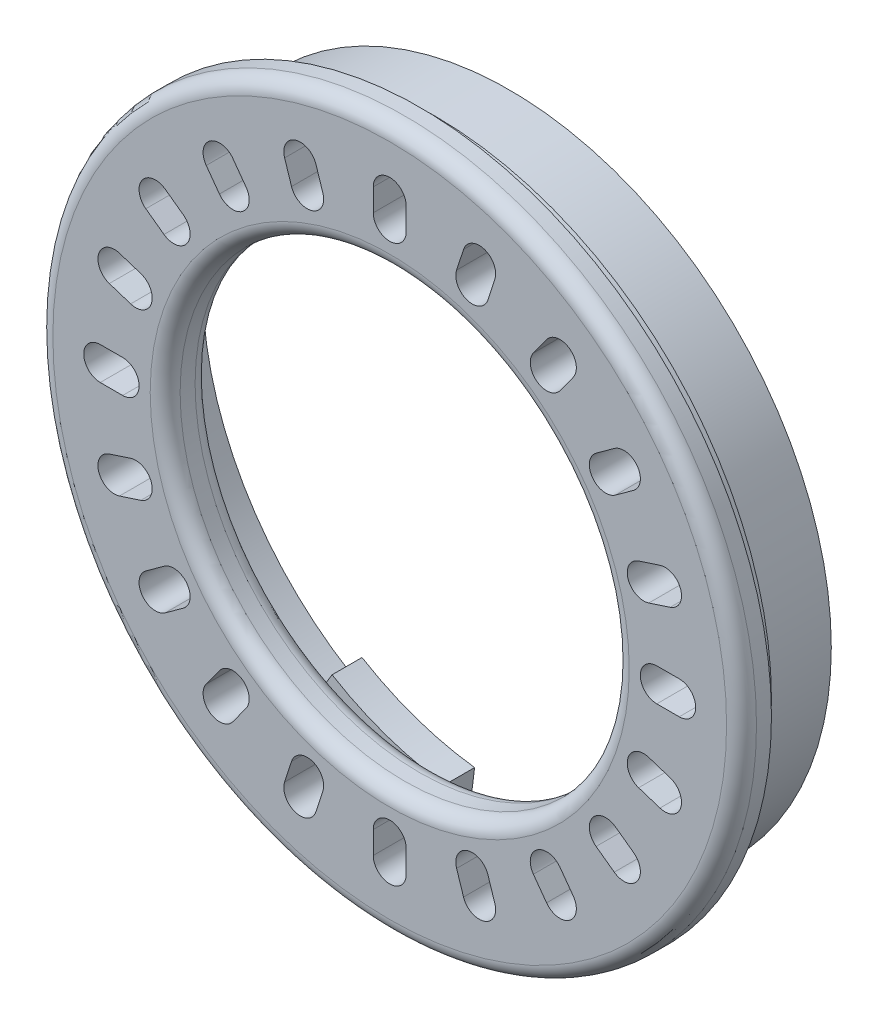
SolidWorks part; units mm, degrees
ref_plane "前视基准面" through (0, 0, 0) normal (0, 0, 1) x (1, 0, 0)
ref_plane "上视基准面" through (0, 0, 0) normal (0, 1, 0) x (1, 0, 0)
ref_plane "右视基准面" through (0, 0, 0) normal (1, 0, 0) x (0, 0, -1)
sketch "草图1" plane through (0, 0, 0) normal (0, 0, 1) x (1, 0, 0)
  circle A0 centre (0, 0) radius 23.5157
  circle A2 centre (0, 0) radius 15.01
  dimension "D1" = 30.02
extrude "凸台-拉伸1" add sketch "草图1" along normal blind 3
sketch "草图2" plane through (0, 0, 0) normal (0, 0, -1) x (-1, 0, 0)
  circle A7 centre (0, 0) radius 22.5157
  circle A8 centre (0, 0) radius 23.5157
  circle A9 centre (0, 0) radius 23.5157
  dimension "D1" = 0
  dimension "D2" = 1
extrude "切除-拉伸3" cut sketch "草图2" against normal blind 1
fillet "圆角1" radius 1 1 edges at (23.5157, 0, 3)
fillet "圆角2" radius 1 1 edges at (15.01, 0, 3)
fillet "圆角3" radius 1 1 edges at (15.01, 0, 0)
sketch "草图3" plane through (0, 0, 3) normal (0, 0, 1) x (1, 0, 0)
  line L0 (5.9795, 18.4029) -> (5.516, 16.9764) construction
  line L1 (0, 19.35) -> (0, 17.85) construction
  line L2 (1.1, 19.35) -> (1.1, 17.85)
  line L5 (-1.1, 19.35) -> (-1.1, 17.85)
  line L8 (7.0256, 18.063) -> (6.5621, 16.6364)
  line L17 (4.9333, 18.7429) -> (4.4698, 17.3163)
  line L26 (11.3736, 15.6545) -> (10.492, 14.441) construction
  line L35 (12.2636, 15.0079) -> (11.3819, 13.7944)
  line L44 (10.4837, 16.301) -> (9.602, 15.0875)
  line L53 (15.6545, 11.3736) -> (14.441, 10.492) construction
  line L62 (16.301, 10.4837) -> (15.0875, 9.602)
  line L65 (15.0079, 12.2636) -> (13.7944, 11.3819)
  line L68 (18.4029, 5.9795) -> (16.9764, 5.516) construction
  line L71 (18.7429, 4.9333) -> (17.3163, 4.4698)
  line L74 (18.063, 7.0256) -> (16.6364, 6.5621)
  line L77 (19.35, 0) -> (17.85, 0) construction
  line L80 (19.35, -1.1) -> (17.85, -1.1)
  line L83 (19.35, 1.1) -> (17.85, 1.1)
  line L86 (18.4029, -5.9795) -> (16.9764, -5.516) construction
  line L89 (18.063, -7.0256) -> (16.6364, -6.5621)
  line L92 (18.7429, -4.9333) -> (17.3163, -4.4698)
  line L95 (15.6545, -11.3736) -> (14.441, -10.492) construction
  line L98 (15.0079, -12.2636) -> (13.7944, -11.3819)
  line L101 (16.301, -10.4837) -> (15.0875, -9.602)
  line L102 (11.3736, -15.6545) -> (10.492, -14.441) construction
  line L103 (10.4837, -16.301) -> (9.602, -15.0875)
  line L104 (12.2636, -15.0079) -> (11.3819, -13.7944)
  line L105 (5.9795, -18.4029) -> (5.516, -16.9764) construction
  line L106 (4.9333, -18.7429) -> (4.4698, -17.3163)
  line L107 (7.0256, -18.063) -> (6.5621, -16.6364)
  line L108 (0, -19.35) -> (0, -17.85) construction
  line L109 (-1.1, -19.35) -> (-1.1, -17.85)
  line L110 (1.1, -19.35) -> (1.1, -17.85)
  line L111 (-5.9795, -18.4029) -> (-5.516, -16.9764) construction
  line L112 (-7.0256, -18.063) -> (-6.5621, -16.6364)
  line L113 (-4.9333, -18.7429) -> (-4.4698, -17.3163)
  line L114 (-11.3736, -15.6545) -> (-10.492, -14.441) construction
  line L115 (-12.2636, -15.0079) -> (-11.3819, -13.7944)
  line L116 (-10.4837, -16.301) -> (-9.602, -15.0875)
  line L117 (-15.6545, -11.3736) -> (-14.441, -10.492) construction
  line L118 (-16.301, -10.4837) -> (-15.0875, -9.602)
  line L119 (-15.0079, -12.2636) -> (-13.7944, -11.3819)
  line L120 (-18.4029, -5.9795) -> (-16.9764, -5.516) construction
  line L121 (-18.7429, -4.9333) -> (-17.3163, -4.4698)
  line L122 (-18.063, -7.0256) -> (-16.6364, -6.5621)
  line L123 (-19.35, 0) -> (-17.85, 0) construction
  line L124 (-19.35, 1.1) -> (-17.85, 1.1)
  line L125 (-19.35, -1.1) -> (-17.85, -1.1)
  line L126 (-18.4029, 5.9795) -> (-16.9764, 5.516) construction
  line L127 (-18.063, 7.0256) -> (-16.6364, 6.5621)
  line L128 (-18.7429, 4.9333) -> (-17.3163, 4.4698)
  line L129 (-15.6545, 11.3736) -> (-14.441, 10.492) construction
  line L130 (-15.0079, 12.2636) -> (-13.7944, 11.3819)
  line L131 (-16.301, 10.4837) -> (-15.0875, 9.602)
  line L132 (-11.3736, 15.6545) -> (-10.492, 14.441) construction
  line L133 (-10.4837, 16.301) -> (-9.602, 15.0875)
  line L134 (-12.2636, 15.0079) -> (-11.3819, 13.7944)
  line L135 (-5.9795, 18.4029) -> (-5.516, 16.9764) construction
  line L136 (-4.9333, 18.7429) -> (-4.4698, 17.3163)
  line L137 (-7.0256, 18.063) -> (-6.5621, 16.6364)
  arc A42 (1.1, 19.35) -> (-1.1, 19.35) centre (0, 19.35) ccw
  arc A43 (-1.1, 17.85) -> (1.1, 17.85) centre (0, 17.85) ccw
  circle A82 centre (0, 0) radius 16.01 construction
  arc A83 (7.0256, 18.063) -> (4.9333, 18.7429) centre (5.9795, 18.4029) ccw
  arc A84 (4.4698, 17.3163) -> (6.5621, 16.6364) centre (5.516, 16.9764) ccw
  arc A85 (12.2636, 15.0079) -> (10.4837, 16.301) centre (11.3736, 15.6545) ccw
  arc A86 (9.602, 15.0875) -> (11.3819, 13.7944) centre (10.492, 14.441) ccw
  arc A87 (16.301, 10.4837) -> (15.0079, 12.2636) centre (15.6545, 11.3736) ccw
  arc A88 (13.7944, 11.3819) -> (15.0875, 9.602) centre (14.441, 10.492) ccw
  arc A89 (18.7429, 4.9333) -> (18.063, 7.0256) centre (18.4029, 5.9795) ccw
  arc A90 (16.6364, 6.5621) -> (17.3163, 4.4698) centre (16.9764, 5.516) ccw
  arc A91 (19.35, -1.1) -> (19.35, 1.1) centre (19.35, 0) ccw
  arc A92 (17.85, 1.1) -> (17.85, -1.1) centre (17.85, 0) ccw
  arc A93 (18.063, -7.0256) -> (18.7429, -4.9333) centre (18.4029, -5.9795) ccw
  arc A94 (17.3163, -4.4698) -> (16.6364, -6.5621) centre (16.9764, -5.516) ccw
  arc A95 (15.0079, -12.2636) -> (16.301, -10.4837) centre (15.6545, -11.3736) ccw
  arc A96 (15.0875, -9.602) -> (13.7944, -11.3819) centre (14.441, -10.492) ccw
  arc A97 (10.4837, -16.301) -> (12.2636, -15.0079) centre (11.3736, -15.6545) ccw
  arc A98 (11.3819, -13.7944) -> (9.602, -15.0875) centre (10.492, -14.441) ccw
  arc A99 (4.9333, -18.7429) -> (7.0256, -18.063) centre (5.9795, -18.4029) ccw
  arc A100 (6.5621, -16.6364) -> (4.4698, -17.3163) centre (5.516, -16.9764) ccw
  arc A101 (-1.1, -19.35) -> (1.1, -19.35) centre (0, -19.35) ccw
  arc A102 (1.1, -17.85) -> (-1.1, -17.85) centre (0, -17.85) ccw
  arc A103 (-7.0256, -18.063) -> (-4.9333, -18.7429) centre (-5.9795, -18.4029) ccw
  arc A104 (-4.4698, -17.3163) -> (-6.5621, -16.6364) centre (-5.516, -16.9764) ccw
  arc A105 (-12.2636, -15.0079) -> (-10.4837, -16.301) centre (-11.3736, -15.6545) ccw
  arc A106 (-9.602, -15.0875) -> (-11.3819, -13.7944) centre (-10.492, -14.441) ccw
  arc A107 (-16.301, -10.4837) -> (-15.0079, -12.2636) centre (-15.6545, -11.3736) ccw
  arc A108 (-13.7944, -11.3819) -> (-15.0875, -9.602) centre (-14.441, -10.492) ccw
  arc A109 (-18.7429, -4.9333) -> (-18.063, -7.0256) centre (-18.4029, -5.9795) ccw
  arc A110 (-16.6364, -6.5621) -> (-17.3163, -4.4698) centre (-16.9764, -5.516) ccw
  arc A111 (-19.35, 1.1) -> (-19.35, -1.1) centre (-19.35, 0) ccw
  arc A112 (-17.85, -1.1) -> (-17.85, 1.1) centre (-17.85, 0) ccw
  arc A113 (-18.063, 7.0256) -> (-18.7429, 4.9333) centre (-18.4029, 5.9795) ccw
  arc A114 (-17.3163, 4.4698) -> (-16.6364, 6.5621) centre (-16.9764, 5.516) ccw
  arc A115 (-15.0079, 12.2636) -> (-16.301, 10.4837) centre (-15.6545, 11.3736) ccw
  arc A116 (-15.0875, 9.602) -> (-13.7944, 11.3819) centre (-14.441, 10.492) ccw
  arc A117 (-10.4837, 16.301) -> (-12.2636, 15.0079) centre (-11.3736, 15.6545) ccw
  arc A118 (-11.3819, 13.7944) -> (-9.602, 15.0875) centre (-10.492, 14.441) ccw
  arc A119 (-4.9333, 18.7429) -> (-7.0256, 18.063) centre (-5.9795, 18.4029) ccw
  arc A120 (-6.5621, 16.6364) -> (-4.4698, 17.3163) centre (-5.516, 16.9764) ccw
  point P7 (5.7477, 17.6897)
  point P9 (0, 18.6)
  point P20 (10.9328, 15.0477)
  point P27 (15.0477, 10.9328)
  point P34 (17.6897, 5.7477)
  point P41 (18.6, 0)
  point P48 (17.6897, -5.7477)
  point P55 (15.0477, -10.9328)
  point P62 (10.9328, -15.0477)
  point P69 (5.7477, -17.6897)
  point P76 (0, -18.6)
  point P83 (-5.7477, -17.6897)
  point P90 (-10.9328, -15.0477)
  point P97 (-15.0477, -10.9328)
  point P104 (-17.6897, -5.7477)
  point P111 (-18.6, 0)
  point P118 (-17.6897, 5.7477)
  point P125 (-15.0477, 10.9328)
  point P132 (-10.9328, 15.0477)
  point P139 (-5.7477, 17.6897)
  point P144 (0, 0)
  point P150 (-0.7039, -0.6961)
  dimension "D1" = 1.5
  dimension "D3" = 2.2
  dimension "D4" = 18.6
extrude "切除-拉伸4" cut sketch "草图3" against normal through all
sketch "草图5" plane through (0, 0, 0) normal (0, 0, -1) x (-1, 0, 0)
  circle A0 centre (0, 0) radius 20.5157
  circle A1 centre (0, 0) radius 21.5157
  circle A3 centre (0, 0) radius 22.5157 construction
  dimension "D1" = 1
  dimension "D2" = 1
extrude "凸台-拉伸2" add sketch "草图5" along normal blind 5
sketch "草图6" plane through (0, 0, -5) normal (0, 0, -1) x (-1, 0, 0)
  line L6 (-16.2691, -9.8527) -> (-18.354, -11.1153)
  line L7 (-18.8771, -2.3269) -> (-21.2962, -2.6251)
  line L8 (-9.8527, 16.2691) -> (-11.1153, 18.354)
  line L9 (-2.3269, 18.8771) -> (-2.6251, 21.2962)
  line L10 (16.2691, 9.8527) -> (18.354, 11.1153)
  line L11 (18.8771, 2.3269) -> (21.2962, 2.6251)
  line L12 (9.8527, -16.2691) -> (11.1153, -18.354)
  line L13 (2.3269, -18.8771) -> (2.6251, -21.2962)
  arc A0 (-21.2962, -2.6251) -> (-18.354, -11.1153) centre (0, 0) ccw
  arc A1 (-18.8771, -2.3269) -> (-16.2691, -9.8527) centre (0, 0) ccw
  arc A2 (-18.825, -2.573) -> (-18.4502, -4.5376) centre (0, 0) ccw construction
  arc A7 (-2.6251, 21.2962) -> (-11.1153, 18.354) centre (0, 0) ccw
  arc A8 (-2.3269, 18.8771) -> (-9.8527, 16.2691) centre (0, 0) ccw
  arc A9 (21.2962, 2.6251) -> (18.354, 11.1153) centre (0, 0) ccw
  arc A10 (18.8771, 2.3269) -> (16.2691, 9.8527) centre (0, 0) ccw
  arc A11 (2.6251, -21.2962) -> (11.1153, -18.354) centre (0, 0) ccw
  arc A12 (2.3269, -18.8771) -> (9.8527, -16.2691) centre (0, 0) ccw
  point P21 (0, 0)
  point P25 (0, 0)
  dimension "D1" = 0.02
  dimension "D2" = 4
extrude "凸台-拉伸3" add sketch "草图6" against normal blind 2
